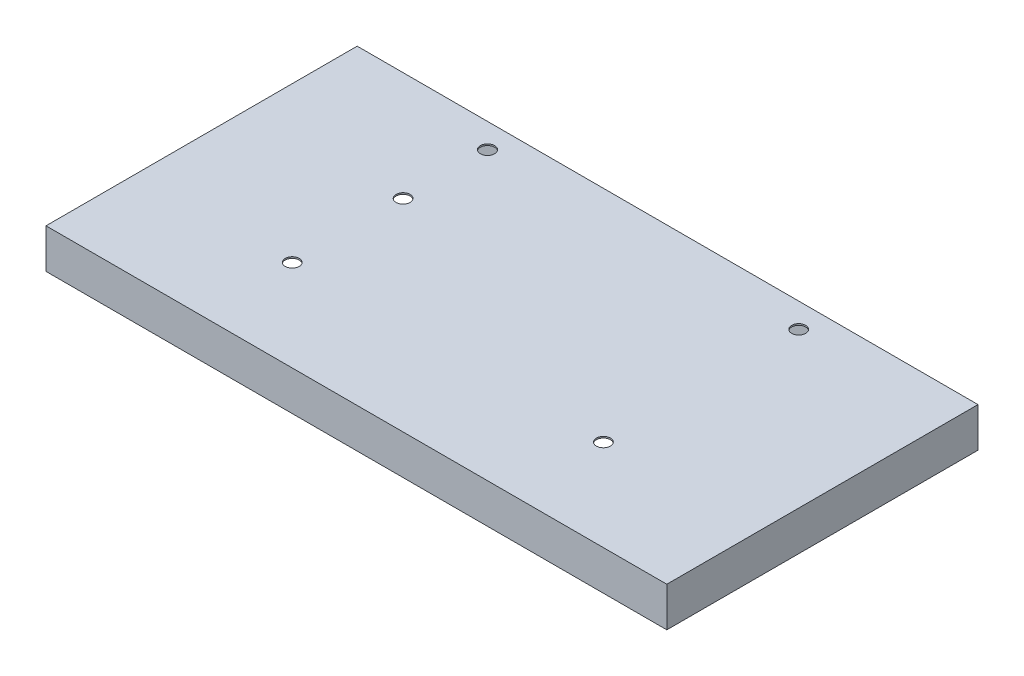
SolidWorks part; units mm, degrees
ref_plane "Alzado" through (0, 0, 0) normal (0, 0, 1) x (1, 0, 0)
ref_plane "Planta" through (0, 0, 0) normal (0, 1, 0) x (1, 0, 0)
ref_plane "Vista lateral" through (0, 0, 0) normal (1, 0, 0) x (0, 0, -1)
sketch "Croquis1" plane through (0, 0, 0) normal (0, 1, 0) x (1, 0, 0)
  line L1 (-399, 200) -> (399, 200)
  line L2 (-399, 200) -> (-399, -200)
  line L3 (-399, -200) -> (399, -200)
  line L4 (399, 200) -> (399, -200)
  line L5 (-399, 200) -> (399, -200) construction
  line L6 (-399, -200) -> (399, 200) construction
  point P0 (0, 0)
  dimension "D1" = 798
  dimension "D2" = 400
extrude "Saliente-Extruir1" add sketch "Croquis1" along normal blind 50.8
shell "Vaciado1" thickness 1.9
sketch "Croquis2" plane through (0, 50.8, 0) normal (0, 1, 0) x (1, 0, 0)
  line L0 (0, 0) -> (-238.4485, 0) construction
  line L1 (-238.4485, 0) -> (-238.4485, 141.0252) construction
  line L2 (0, 0) -> (0, 70.5126) construction
  circle A0 centre (-238.4485, 141.0252) radius 10.9005
  circle A1 centre (-238.4485, -165.5514) radius 9.8256
  circle A2 centre (196.209, 141.0252) radius 8.1754
  circle A3 centre (196.209, -165.5514) radius 9.5379
sketch "Croquis3" plane through (0, 50.8, 0) normal (0, 1, 0) x (1, 0, 0)
  circle A1 centre (200, -82.5) radius 9
  circle A2 centre (200, 168.5) radius 9
  circle A3 centre (-200, -82.5) radius 9
  circle A4 centre (-200, 60) radius 9
  circle A5 centre (-200, 168.5) radius 9.1788
extrude "Cortar-Extruir1" cut sketch "Croquis3" against normal blind 10
sketch "Croquis5" plane through (0, 50.8, 0) normal (0, 1, 0) x (1, 0, 0)
  line L0 (-399, 200) -> (-399, -200)
  line L1 (-399, -200) -> (399, -200)
  line L2 (399, -200) -> (399, 200)
  line L3 (399, 200) -> (-399, 200)
  circle A0 centre (-200, 168.5) radius 3.9692
  circle A1 centre (-200, 60) radius 3.7194
  circle A2 centre (-200, -82.5) radius 5.6499
  circle A3 centre (200, -82.5) radius 5.0914
  circle A4 centre (200, 168.5) radius 4.3034
